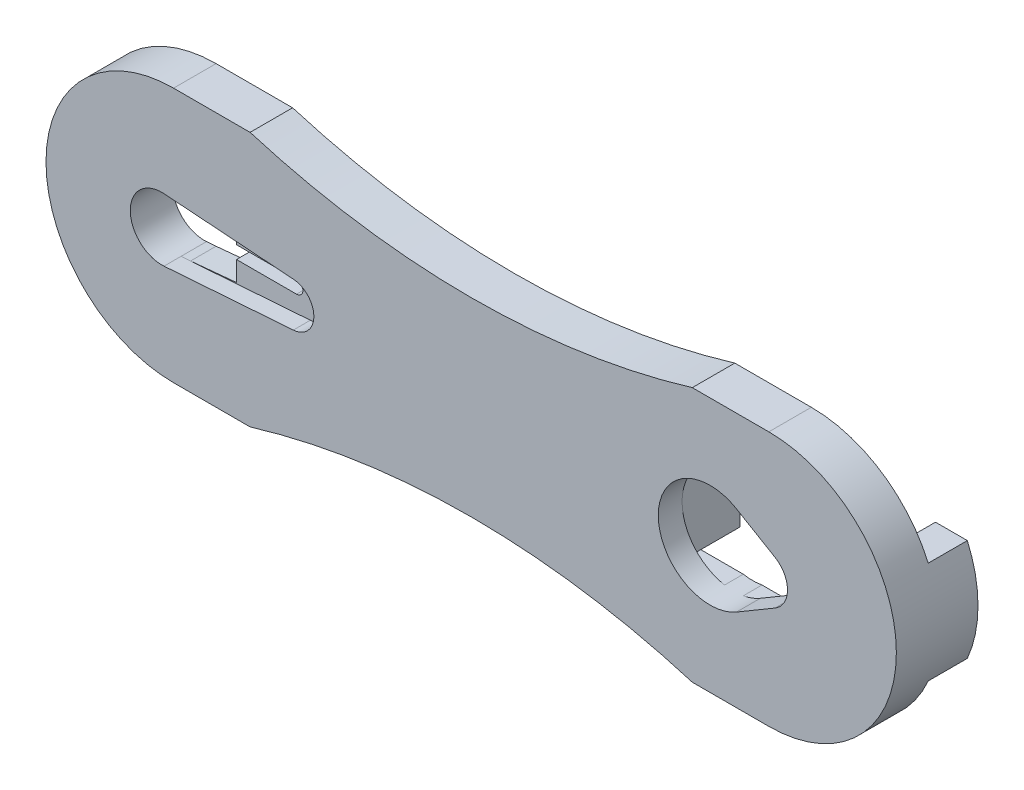
SolidWorks part; units mm, degrees
ref_plane "Front Plane" through (0, 0, 0) normal (0, 0, 1) x (1, 0, 0)
ref_plane "Top Plane" through (0, 0, 0) normal (0, 1, 0) x (1, 0, 0)
ref_plane "Right Plane" through (0, 0, 0) normal (1, 0, 0) x (0, 0, -1)
ref_plane "Plane1" through (0, 0, 0) normal (0, 0, -1) x (-1, 0, 0)
sketch "Sketch1" plane through (0, 0, 0) normal (0, 0, -1) x (-1, 0, 0)
  line L0 (-70, 0) -> (-61, 0)
  line L1 (0, 0) -> (-9, 0)
  line L2 (0, -15) -> (-10.6343, -15) construction
  line L3 (0, -30) -> (-9, -30)
  line L4 (-70, -30) -> (-61, -30)
  line L5 (0, -11.4) -> (-5.4, -11.905)
  line L6 (3.6, -15) -> (3.6, -20.4896) construction
  line L7 (0, -18.6) -> (-5.4, -18.095)
  line L8 (-5.4, -11.905) -> (-5.4, -18.095)
  arc A1 (-61, 0) -> (-9, 0) centre (-35, 86.1626) ccw
  arc A2 (-61, -30) -> (-9, -30) centre (-35, -116.1626) cw
  arc A9 (0, -11.4) -> (0, -18.6) centre (0, -15) cw
  arc A11 (-70, 0) -> (-70, -30) centre (-70, -15) ccw
  arc A15 (0, -30) -> (0, 0) centre (0, -15) ccw
  dimension "D1" = 7.2
  dimension "D2" = 9
  dimension "D3" = 90
  dimension "D4" = 9
  dimension "D5" = 6.19
  dimension "D10" = 15
  dimension "D11" = 100
extrude "Boss-Extrude1" add sketch "Sketch1" against normal blind 5
sketch "Croquis1" plane through (0, 0, 5) normal (0, 0, 1) x (1, 0, 0)
  line L0 (-1.1238, -11.3096) -> (14.0871, -12.4067)
  line L1 (14.0871, -17.5933) -> (-1.1238, -18.6904)
  circle A0 centre (0, -15) radius 3.6 construction
  arc A1 (14.0871, -12.4067) -> (14.0871, -17.5933) centre (13.9, -15) cw
  circle A2 centre (0, -15) radius 3.6
  arc A4 (-1.1238, -11.3096) -> (-1.1238, -18.6904) centre (-1.39, -15) ccw
  dimension "D1" = 2.6
  dimension "D2" = 16.5
  dimension "D3" = 3.7
sketch "Croquis3" plane through (0, 0, 0) normal (0, 0, -1) x (-1, 0, 0)
  line L1 (-80, -9) -> (-57, -9)
  line L2 (-80, -9) -> (-80, -21)
  line L3 (-80, -21) -> (-57, -21)
  line L4 (-57, -9) -> (-57, -21)
  arc A0 (0, -30) -> (0, 0) centre (0, -15) ccw construction
  arc A5 (-70, 0) -> (-70, -30) centre (-70, -15) ccw construction
  point P7 (15, -15)
  point P8 (-57, -15)
  dimension "D1" = 23
  dimension "D2" = 12
  dimension "D3" = 5
extrude "Cortar-Extruir2" cut sketch "Croquis3" against normal blind 2.2
sketch "Croquis4" plane through (0, 0, 2.2) normal (0, 0, -1) x (-1, 0, 0)
  line L0 (-66.2, -9.7464) -> (-70.7246, -12.4163)
  line L1 (-66.2, -20.2536) -> (-70.7246, -17.5837)
  line L2 (-57, -21) -> (-57, -9) construction
  arc A1 (-66.2, -20.2536) -> (-66.2, -9.7464) centre (-63.1, -15) ccw
  arc A3 (-70.7246, -12.4163) -> (-70.7246, -17.5837) centre (-69.2, -15) ccw
  point P12 (-57, -15)
  dimension "D1" = 3
  dimension "D2" = 12.2
  dimension "D4" = 15.2
extrude "Cortar-Extruir3" cut sketch "Croquis4" against normal through all both and the other way through all
sketch "Croquis6" [suppressed] plane through (0, 0, 2.2) normal (0, 0, -1) x (-1, 0, 0)
  circle A0 centre (-52.5, -20.715) radius 1.5
  arc A2 (-66.2, -20.2536) -> (-64.2, -21) centre (-63.1, -15) ccw construction
  circle A3 centre (-78.7, -15) radius 1.5
  arc A4 (-70.7246, -12.4163) -> (-70.7246, -17.5837) centre (-69.2, -15) ccw construction
  point P11 (-65.2329, -20.715)
  point P12 (-72.2, -15)
  dimension "D1" = 3
  dimension "D2" = 5
  dimension "D3" = 3
  dimension "D4" = 3
sketch "Sketch2" [suppressed] plane through (0, 0, 5) normal (0, 0, 1) x (1, 0, 0)
  line L1 (88.7475, -39.7589) -> (19.0099, -39.7589)
  line L2 (88.7475, -39.7589) -> (88.7475, 9.9653)
  line L3 (88.7475, 9.9653) -> (19.0099, 9.9653)
  line L4 (19.0099, -39.7589) -> (19.0099, 9.9653)
  line L5 (88.7475, -39.7589) -> (19.0099, 9.9653) construction
  line L6 (88.7475, 9.9653) -> (19.0099, -39.7589) construction
  point P0 (53.8787, -14.8968)
extrude "Cut-Extrude1" [suppressed] cut sketch "Sketch2" against normal through all both and the other way through all
sketch "Sketch3" [suppressed] plane through (0, 0, 5) normal (0, 0, 1) x (1, 0, 0)
  line L1 (42.9651, -39.6558) -> (-20.3981, -39.6558)
  line L2 (42.9651, -39.6558) -> (42.9651, 7.1799)
  line L3 (42.9651, 7.1799) -> (-20.3981, 7.1799)
  line L4 (-20.3981, -39.6558) -> (-20.3981, 7.1799)
  line L5 (42.9651, -39.6558) -> (-20.3981, 7.1799) construction
  line L6 (42.9651, 7.1799) -> (-20.3981, -39.6558) construction
  point P0 (11.2835, -16.2379)
extrude "Cut-Extrude2" [suppressed] cut sketch "Sketch3" against normal through all both and the other way through all
sketch "Sketch4" plane through (0, 0, 0) normal (0, 0, -1) x (-1, 0, 0)
  line L0 (-64.2, -9) -> (-80, -9) construction
  line L1 (-56, -22) -> (-81, -22)
  line L2 (-56, -22) -> (-56, -8)
  line L3 (-56, -8) -> (-81, -8)
  line L4 (-81, -22) -> (-81, -8)
  line L5 (-56, -22) -> (-81, -8) construction
  line L6 (-56, -8) -> (-81, -22) construction
  line L7 (-80, -9) -> (-80, -21) construction
  line L8 (-57, -21) -> (-57, -9) construction
  line L9 (-80, -21) -> (-64.2, -21) construction
  point P0 (-68.5, -15)
  dimension "D1" = 1
  dimension "D2" = 1
  dimension "D3" = 1
  dimension "D4" = 1
extrude "Cut-Extrude3" [suppressed] cut sketch "Sketch4" against normal through all both and the other way through all flip side to cut
sketch "Sketch6" plane through (0, 0, 5) normal (0, 0, 1) x (1, 0, 0)
  line L2 (14.0871, -12.4067) -> (-1.1238, -11.3096)
  line L3 (-1.1238, -18.6904) -> (14.0871, -17.5933)
  line L4 (14.0871, -12.4067) -> (-1.1238, -11.3096)
  line L5 (-1.1238, -18.6904) -> (14.0871, -17.5933)
  arc A4 (14.0871, -17.5933) -> (14.0871, -12.4067) centre (13.9, -15) ccw
  arc A5 (-1.1238, -11.3096) -> (-1.1238, -18.6904) centre (-1.39, -15) ccw
  arc A6 (14.0871, -17.5933) -> (14.0871, -12.4067) centre (13.9, -15) ccw
  arc A7 (-1.1238, -11.3096) -> (-1.1238, -18.6904) centre (-1.39, -15) ccw
  dimension "D2" = 0
extrude "Cut-Extrude4" cut sketch "Sketch6" against normal blind 2 and the other way through all
sketch "Sketch7" plane through (0, 0, 5) normal (0, 0, 1) x (1, 0, 0)
  line L1 (17.0468, -20.0398) -> (-5.5875, -20.0398)
  line L2 (17.0468, -20.0398) -> (17.0468, -10.2872)
  line L3 (17.0468, -10.2872) -> (-5.5875, -10.2872)
  line L4 (-5.5875, -20.0398) -> (-5.5875, -10.2872)
  line L5 (17.0468, -20.0398) -> (-5.5875, -10.2872) construction
  line L6 (17.0468, -10.2872) -> (-5.5875, -20.0398) construction
  point P0 (5.7297, -15.1635)
extrude "Cut-Extrude5" [suppressed] cut sketch "Sketch7" against normal through all flip side to cut
sketch "Sketch8" plane through (0, 0, 3) normal (0, 0, 1) x (1, 0, 0)
  line L0 (-1.1238, -11.3096) -> (0, -11.4)
  line L1 (-1.1238, -18.6904) -> (0, -18.6)
  arc A0 (0, -11.4) -> (0, -18.6) centre (0, -15) ccw construction
  arc A1 (0, -11.4) -> (0, -18.6) centre (0, -15) ccw
  arc A2 (-1.1238, -11.3096) -> (-1.1238, -18.6904) centre (-1.39, -15) ccw construction
  arc A3 (-1.1238, -11.3096) -> (-1.1238, -18.6904) centre (-1.39, -15) ccw
extrude "Cut-Extrude6" cut sketch "Sketch8" against normal through all
sketch "Sketch9" plane through (0, 0, 0) normal (0, 0, -1) x (-1, 0, 0)
  line L0 (-80, -21) -> (-64.2, -21) construction
  line L1 (-83.7477, -21) -> (-80, -21)
  line L3 (-83.7477, -9) -> (-80, -9)
  line L4 (-80, -21) -> (-80, -9)
  line L7 (-80, -15) -> (-57, -15) construction
  line L8 (-68.5, -15) -> (-68.5, -4.7031) construction
  line L9 (-52, -9) -> (-57, -9)
  line L10 (-57, -21) -> (-57, -9)
  line L11 (-52, -21) -> (-57, -21)
  line L12 (-52, -21) -> (-52, -9)
  arc A0 (-57, -15) -> (-62, -9) centre (-63.1, -15) ccw construction
  arc A1 (-70, 0) -> (-70, -30) centre (-70, -15) ccw construction
  arc A2 (-83.7477, -9) -> (-83.7477, -21) centre (-70, -15) ccw
  point P2 (0, 0)
  dimension "D1" = 5
extrude "Boss-Extrude2" add sketch "Sketch9" along normal blind 4.6
sketch "Sketch10" plane through (0, 0, -4.6) normal (0, 0, -1) x (-1, 0, 0)
  line L0 (-80, -15) -> (-57, -15) construction
  line L1 (-80, -9) -> (-80, -21) construction
  line L2 (-57, -9) -> (-57, -21) construction
  line L3 (-68.5, -15) -> (-68.5, -4.9258) construction
  circle A0 centre (-54.44, -15) radius 0.9
  circle A1 centre (-54.44, -15) radius 2.56 construction
  circle A2 centre (-82.56, -15) radius 0.9
  point P11 (0, 0)
  point P12 (0, 0)
  point P13 (0, 0)
  dimension "D1" = 1.8
  dimension "D2" = 5.12
extrude "Cut-Extrude7" cut sketch "Sketch10" against normal blind 8
sketch "Sketch11" plane through (0, 0, 3) normal (0, 0, 1) x (1, 0, 0)
  line L0 (4.96, -14.25) -> (12.46, -14.25)
  line L1 (12.46, -15.75) -> (4.96, -15.75)
  line L2 (4.96, -15.75) -> (4.96, -14.25)
  line L3 (5.4, -15) -> (-5.09, -15) construction
  line L4 (5.4, -11.905) -> (5.4, -18.095) construction
  circle A0 centre (12.46, -15) radius 0.75 construction
  arc A1 (-1.1238, -11.3096) -> (-1.1238, -18.6904) centre (-1.39, -15) ccw construction
  circle A4 centre (4.96, -15) radius 0.75 construction
  arc A5 (12.46, -14.25) -> (12.46, -15.75) centre (12.46, -15) cw
  circle A6 centre (7.46, -15) radius 0.75 construction
  circle A7 centre (9.96, -15) radius 0.75 construction
  point P7 (0, 0)
  dimension "D1" = 1.5
  dimension "D2" = 16.8
  dimension "D4" = 7.5
  dimension "D3" = 4
extrude "Cut-Extrude8" cut sketch "Sketch11" against normal through all
sketch "Sketch13" plane through (0, 0, -4.6) normal (0, 0, -1) x (-1, 0, 0)
  line L1 (-85.2369, -21.9119) -> (-51.6091, -21.9119)
  line L2 (-85.2369, -21.9119) -> (-85.2369, -8.3976)
  line L3 (-85.2369, -8.3976) -> (-51.6091, -8.3976)
  line L4 (-51.6091, -21.9119) -> (-51.6091, -8.3976)
extrude "Cut-Extrude9" [suppressed] cut sketch "Sketch13" against normal through all flip side to cut
sketch "Sketch14" plane through (0, 0, 5) normal (0, 0, 1) x (1, 0, 0)
  line L1 (17.0783, -20.3657) -> (-5.4547, -20.3657)
  line L2 (17.0783, -20.3657) -> (17.0783, -9.866)
  line L3 (17.0783, -9.866) -> (-5.4547, -9.866)
  line L4 (-5.4547, -20.3657) -> (-5.4547, -9.866)
  line L5 (17.0783, -20.3657) -> (-5.4547, -9.866) construction
  line L6 (17.0783, -9.866) -> (-5.4547, -20.3657) construction
  point P0 (5.8118, -15.1159)
extrude "Cut-Extrude10" [suppressed] cut sketch "Sketch14" against normal through all flip side to cut
equation "\"D1@Sketch4\"=\"D3@Sketch4\""
equation "\"D3@Sketch4\"=\"D4@Sketch4\""
equation "\"D2@Sketch4\"=\"D4@Sketch4\""
